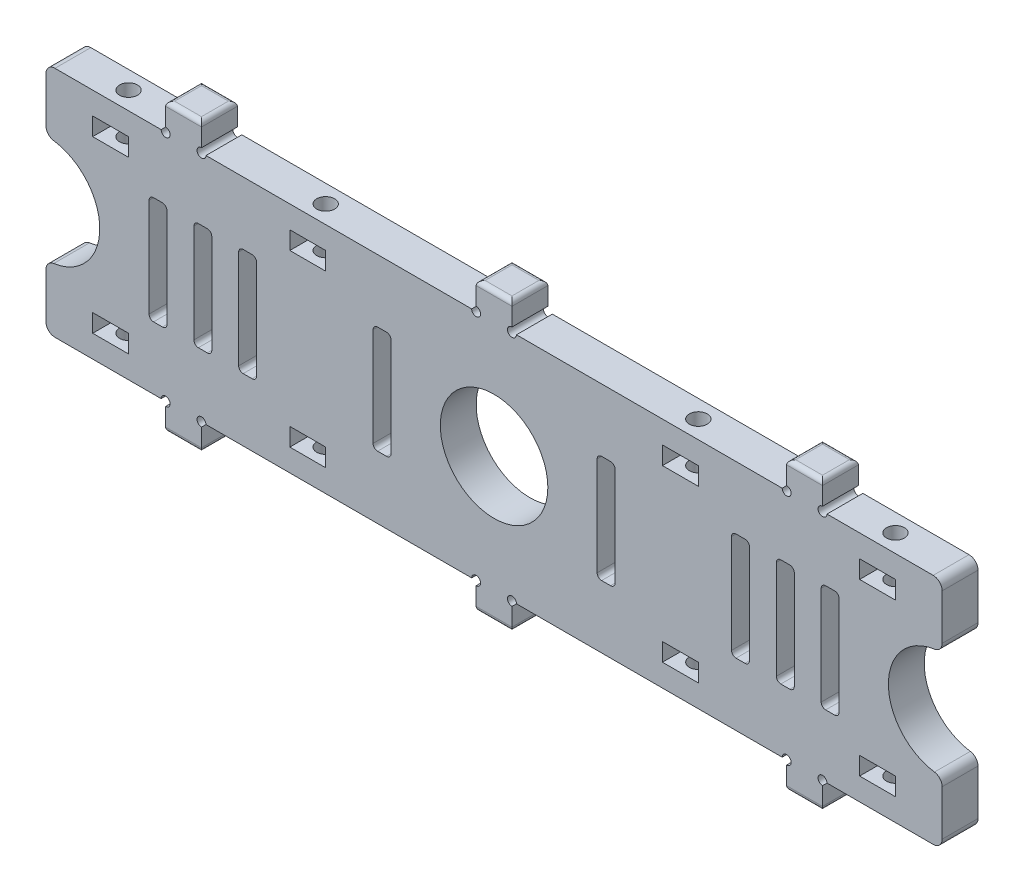
SolidWorks part; units mm, degrees
ref_plane "Front Plane" through (0, 0, 0) normal (0, 0, 1) x (1, 0, 0)
ref_plane "Top Plane" through (0, 0, 0) normal (0, 1, 0) x (1, 0, 0)
ref_plane "Right Plane" through (0, 0, 0) normal (1, 0, 0) x (0, 0, -1)
sketch "Sketch1" plane through (0, 0, 0) normal (0, 0, 1) x (1, 0, 0)
  line L0 (3.6364, -4.2724) -> (6.6364, -4.2724)
  line L1 (-10.2136, 8.7276) -> (1.2864, 8.7276)
  line L2 (-10.2136, 8.7276) -> (-10.2136, -4.2724)
  line L3 (-10.2136, -4.2724) -> (2.6364, -4.2724)
  line L4 (39.7864, 8.7276) -> (39.7864, -4.2724)
  line L5 (39.7864, -4.2724) -> (38.2864, -4.2724)
  line L6 (39.7864, -4.2724) -> (39.7864, -7.2724)
  line L7 (39.7864, -7.2724) -> (37.7864, -7.2724)
  line L8 (37.7864, -4.7724) -> (37.7864, -7.2724)
  line L9 (3.6364, -4.2724) -> (6.6364, -4.2724)
  line L10 (3.1364, -4.7724) -> (3.1364, -7.2724)
  line L11 (3.1364, -7.2724) -> (7.1364, -7.2724)
  line L12 (7.1364, -4.7724) -> (7.1364, -7.2724)
  line L13 (7.6364, -4.2724) -> (37.2864, -4.2724)
  line L14 (38.2864, -4.2724) -> (39.7864, -4.2724)
  line L20 (6.2864, 8.7276) -> (6.2864, 2.7276)
  line L22 (1.2864, 8.7276) -> (1.2864, 2.7276)
  line L23 (1.2864, 2.7276) -> (3.2864, 2.7276)
  line L24 (3.2864, 8.7276) -> (3.2864, 2.7276)
  line L26 (8.2864, 8.7276) -> (8.2864, 2.7276)
  line L27 (6.2864, 2.7276) -> (8.2864, 2.7276)
  line L28 (11.2864, 8.7276) -> (11.2864, 2.7276)
  line L30 (13.2864, 8.7276) -> (13.2864, 2.7276)
  line L31 (11.2864, 2.7276) -> (13.2864, 2.7276)
  line L40 (26.2864, 8.7276) -> (26.2864, 2.7276)
  line L42 (28.2864, 8.7276) -> (28.2864, 2.7276)
  line L43 (26.2864, 2.7276) -> (28.2864, 2.7276)
  line L44 (3.2864, 8.7276) -> (6.2864, 8.7276)
  line L45 (8.2864, 8.7276) -> (11.2864, 8.7276)
  line L46 (13.2864, 8.7276) -> (16.2864, 8.7276)
  line L47 (18.2864, 8.7276) -> (21.2864, 8.7276)
  line L48 (23.2864, 8.7276) -> (26.2864, 8.7276)
  line L49 (28.2864, 8.7276) -> (39.7864, 8.7276)
  line L55 (16.9964, 0.2276) -> (20.9964, 0.2276)
  line L56 (16.9964, 0.2276) -> (16.9964, -1.7724)
  line L57 (16.9964, -1.7724) -> (20.9964, -1.7724)
  line L58 (20.9964, 0.2276) -> (20.9964, -1.7724)
  line L68 (-5.0036, 0.2276) -> (-5.0036, -1.7724)
  line L69 (-5.0036, 0.2276) -> (-1.0036, 0.2276)
  line L70 (-1.0036, 0.2276) -> (-1.0036, -1.7724)
  line L71 (-5.0036, -1.7724) -> (-1.0036, -1.7724)
  line L72 (16.2864, 8.7276) -> (18.2864, 8.7276)
  line L73 (21.2864, 8.7276) -> (23.2864, 8.7276)
  line L74 (16.2864, 8.7276) -> (16.2864, 2.7276) [skipped]
  line L75 (16.2864, 2.7276) -> (18.2864, 2.7276) [skipped]
  line L76 (18.2864, 8.7276) -> (18.2864, 2.7276) [skipped]
  line L78 (21.2864, 8.7276) -> (21.2864, 2.7276) [skipped]
  line L79 (21.2864, 2.7276) -> (23.2864, 2.7276) [skipped]
  line L80 (23.2864, 8.7276) -> (23.2864, 2.7276) [skipped]
  circle A0 centre (-10.2136, 8.7276) radius 6
  circle A1 centre (39.7864, 8.7276) radius 6
  arc A2 (37.7864, -4.7724) -> (37.2864, -4.2724) centre (37.7864, -4.2724) ccw
  arc A3 (7.6364, -4.2724) -> (7.1364, -4.7724) centre (7.1364, -4.2724) ccw
  arc A4 (3.1364, -4.7724) -> (2.6364, -4.2724) centre (3.1364, -4.2724) ccw
  dimension "D8" = 11.5
  dimension "D1" = 13
  dimension "D2" = 50
  dimension "D3" = 3
  dimension "D4" = 2
  dimension "D5" = 30.65
  dimension "D6" = 4
  dimension "D7" = 3
  dimension "D9" = 6
  dimension "D10" = 2
  dimension "D12" = 2
  dimension "D14" = 4
  dimension "D15" = 2
  dimension "D16" = 2.5
  dimension "D17" = 18.79
  dimension "D11" = 6
extrude "Boss-Extrude3" add sketch "Sketch1" along normal blind 4 contours L4 L1 L2 L3 | L12 L3 L10 L11 | L3 L8 L7 L6
fillet "Fillet1" radius 0.5 8 edges at (3.2864, 2.7276, 2) (8.2864, 2.7276, 2) (13.2864, 2.7276, 2) (28.2864, 2.7276, 2) (26.2864, 2.7276, 2) (11.2864, 2.7276, 2) (6.2864, 2.7276, 2) (1.2864, 2.7276, 2)
fillet "Fillet2" radius 1 2 edges at (-10.2136, 2.7276, 2) (-10.2136, -4.2724, 2)
fillet "Fillet3" radius 0.5 7 edges at (38.7864, -7.2724, 0) (38.7864, -7.2724, 4) (37.7864, -7.2724, 2) (7.1364, -7.2724, 2) (5.1364, -7.2724, 0) (5.1364, -7.2724, 4) (3.1364, -7.2724, 2)
sketch "Sketch3" plane through (0, -4.2724, 0) normal (0, -1, 0) x (1, 0, 0)
  line L0 (7.6364, 4) -> (7.6364, 0) construction
  line L1 (7.6364, 0) -> (37.2864, 0) construction
  circle A0 centre (18.9964, 2) radius 1
  circle A1 centre (-3.0036, 2) radius 1
  point P4 (7.6364, 2)
  dimension "D1" = 11.36
  dimension "D2" = 2
  dimension "D3" = 2
extrude "Cut-Extrude1" cut sketch "Sketch3" against normal blind 10 contours A0 | A1
mirror "Mirror3"
mirror "Mirror4" about plane through (0, 8.7276, 4) normal (0, 1, 0) of bodies 106
